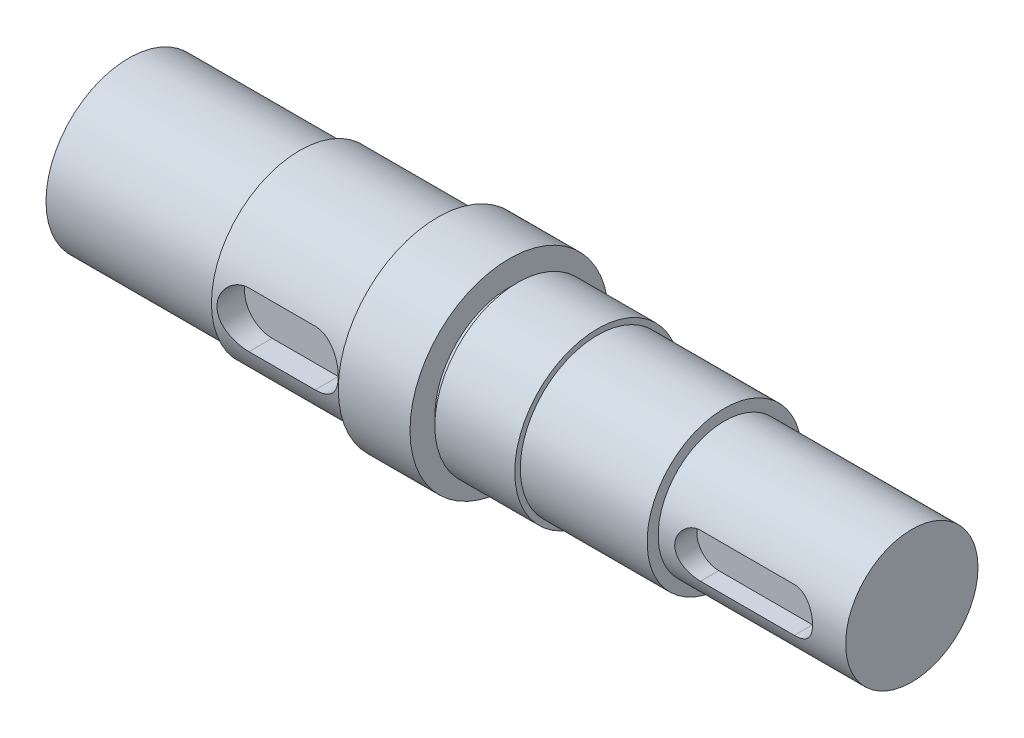
SolidWorks part; units mm, degrees
ref_plane "前视基准面" through (0, 0, 0) normal (0, 0, 1) x (1, 0, 0)
ref_plane "上视基准面" through (0, 0, 0) normal (0, 1, 0) x (1, 0, 0)
ref_plane "右视基准面" through (0, 0, 0) normal (1, 0, 0) x (0, 0, -1)
sketch "草图1" plane through (0, 0, 0) normal (1, 0, 0) x (0, 0, -1)
  circle A0 centre (0, 0) radius 18
  dimension "D1" = 36
extrude "凸台-拉伸1" add sketch "草图1" along normal blind 13
sketch "草图2" plane through (13, 0, 0) normal (1, 0, 0) x (0, 0, -1)
  circle A0 centre (0, 0) radius 13.5
  dimension "D1" = 27
extrude "凸台-拉伸2" add sketch "草图2" along normal blind 1.5
sketch "草图3" plane through (14.5, 0, 0) normal (1, 0, 0) x (0, 0, -1)
  circle A0 centre (0, 0) radius 15
  dimension "D1" = 30
extrude "凸台-拉伸3" add sketch "草图3" along normal blind 14.5
sketch "草图4" plane through (29, 0, 0) normal (1, 0, 0) x (0, 0, -1)
  circle A0 centre (0, 0) radius 14
  dimension "D1" = 28
extrude "凸台-拉伸4" add sketch "草图4" along normal blind 23
sketch "草图5" plane through (52, 0, 0) normal (1, 0, 0) x (0, 0, -1)
  circle A0 centre (0, 0) radius 12
  dimension "D1" = 24
extrude "凸台-拉伸5" add sketch "草图5" along normal blind 34
sketch "草图6" plane through (0, 0, 0) normal (-1, 0, 0) x (0, 0, 1)
  circle A0 centre (0, 0) radius 16
  dimension "D1" = 32
extrude "凸台-拉伸6" add sketch "草图6" along normal blind 25
sketch "草图7" plane through (-25, 0, 0) normal (-1, 0, 0) x (0, 0, 1)
  circle A0 centre (0, 0) radius 15
  dimension "D1" = 30
extrude "凸台-拉伸7" add sketch "草图7" along normal blind 31
sketch "草图8" plane through (0, 0, 0) normal (0, 0, 1) x (1, 0, 0)
  line L0 (-19, 0) -> (-7, 0) construction
  line L1 (-19, -5) -> (-7, -5)
  line L2 (-19, 5) -> (-7, 5)
  line L3 (0, 18) -> (0, -18) construction
  arc A0 (-19, -5) -> (-19, 5) centre (-19, 0) cw
  arc A1 (-7, -5) -> (-7, 5) centre (-7, 0) ccw
  dimension "D1" = 12
  dimension "D4" = 7
  dimension "D2" = 5
  dimension "D3" = 5
extrude "切除-拉伸1" cut sketch "草图8" along normal blind 31 from offset 11
sketch "草图9" plane through (0, 0, 0) normal (0, 0, 1) x (1, 0, 0)
  line L0 (59, 0) -> (76, 0) construction
  line L1 (59, -4) -> (76, -4)
  line L2 (59, 4) -> (76, 4)
  line L3 (52, -14) -> (52, 14) construction
  arc A0 (59, -4) -> (59, 4) centre (59, 0) cw
  arc A1 (76, -4) -> (76, 4) centre (76, 0) ccw
  dimension "D1" = 17
  dimension "D4" = 7
  dimension "D2" = 4
  dimension "D3" = 4
extrude "切除-拉伸2" cut sketch "草图9" along normal blind 31 from offset 8
